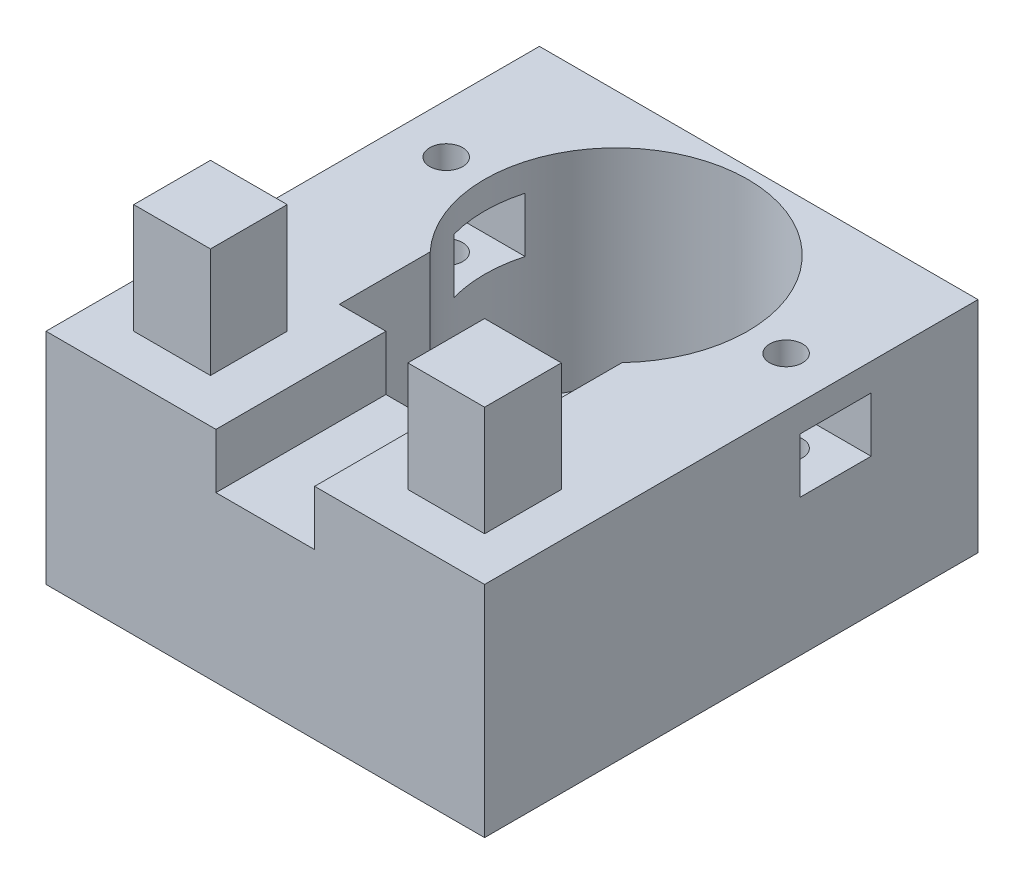
SolidWorks part; units mm, degrees
ref_plane "Plano frontal" through (0, 0, 0) normal (0, 0, 1) x (1, 0, 0)
ref_plane "Plano superior" through (0, 0, 0) normal (0, 1, 0) x (1, 0, 0)
ref_plane "Plano direito" through (0, 0, 0) normal (1, 0, 0) x (0, 0, -1)
sketch "Esboço2" plane through (0, 0, 0) normal (0, 1, 0) x (1, 0, 0)
  line L1 (0, 0) -> (40, 0)
  line L2 (0, 0) -> (0, 45)
  line L3 (0, 45) -> (40, 45)
  line L4 (40, 0) -> (40, 45)
  dimension "D1" = 40
  dimension "D2" = 45
extrude "Corpo" add sketch "Esboço2" along normal blind 20
sketch "Esboço3" plane through (0, 20, 0) normal (0, 1, 0) x (1, 0, 0)
  line L0 (20, -2.1425) -> (20, 46.202) construction
  line L1 (-2.8555, 32) -> (47.4642, 32) construction
  line L2 (40, 0) -> (40, 45) construction
  line L3 (40, 45) -> (0, 45) construction
  line L5 (11.25, 15.5) -> (28.75, 15.5)
  line L6 (11.25, 15.5) -> (11.25, 24.5)
  line L7 (11.25, 24.5) -> (28.75, 24.5)
  line L8 (28.75, 15.5) -> (28.75, 24.5)
  line L9 (11.25, 15.5) -> (28.75, 24.5) construction
  line L10 (11.25, 24.5) -> (28.75, 15.5) construction
  circle A0 centre (20, 32) radius 12
  point P10 (20, 20)
  dimension "D1" = 24
  dimension "D2" = 20
  dimension "D3" = 13
  dimension "D4" = 17.5
  dimension "D5" = 9
  dimension "D6" = 16.5
extrude "Encaixe do Motor" cut sketch "Esboço3" against normal blind 19 contours A0 L7 L6 L5 L8 | L7 A0 | L7 A0
sketch "Esboço5" plane through (0, 20, 0) normal (0, 1, 0) x (1, 0, 0)
  line L0 (41.6655, 32) -> (-3.8205, 32) construction
  line L1 (20, 57.517) -> (20, 6.483) construction
  circle A0 centre (4.5, 32) radius 1.5
  circle A1 centre (35.5, 32) radius 1.5
  point P10 (20, 32)
  dimension "D1" = 3
  dimension "D2" = 3
  dimension "D3" = 15.5
  dimension "D4" = 15.5
extrude "Corte-extrusão2" cut sketch "Esboço5" against normal through all
sketch "Esboço6" plane through (40, 0, 0) normal (1, 0, 0) x (0, 0, -1)
  line L0 (32, 21.0896) -> (32, -1.5414) construction
  line L1 (45, 20) -> (45, 0) construction
  line L2 (0, 20) -> (45, 20) construction
  line L3 (28.75, 17.5) -> (35.25, 17.5)
  line L4 (28.75, 17.5) -> (28.75, 12.5)
  line L5 (28.75, 12.5) -> (35.25, 12.5)
  line L6 (35.25, 17.5) -> (35.25, 12.5)
  line L7 (28.75, 17.5) -> (35.25, 12.5) construction
  line L8 (28.75, 12.5) -> (35.25, 17.5) construction
  point P4 (32, 15)
  dimension "D1" = 13
  dimension "D2" = 6.5
  dimension "D3" = 5
  dimension "D4" = 5
extrude "Corte-extrusão3" cut sketch "Esboço6" against normal through all
sketch "Esboço7" plane through (0, 20, 0) normal (0, 1, 0) x (1, 0, 0)
  line L0 (20, 16.9507) -> (20, -1.8604) construction
  line L1 (40, 0) -> (40, 45) construction
  line L3 (15.5, -3.2615) -> (24.5, -3.2615)
  line L4 (15.5, -3.2615) -> (15.5, 18.3519)
  line L5 (15.5, 18.3519) -> (24.5, 18.3519)
  line L6 (24.5, -3.2615) -> (24.5, 18.3519)
  line L7 (15.5, -3.2615) -> (24.5, 18.3519) construction
  line L8 (15.5, 18.3519) -> (24.5, -3.2615) construction
  point P4 (20, 7.5452)
  dimension "D1" = 20
  dimension "D2" = 9
extrude "Corte-extrusão4" cut sketch "Esboço7" against normal blind 5
sketch "Esboço8" plane through (0, 20, 0) normal (0, 1, 0) x (1, 0, 0)
  line L0 (24.5, 0) -> (40, 0) construction
  line L1 (29, 11) -> (36, 11)
  line L2 (29, 11) -> (29, 4)
  line L3 (29, 4) -> (36, 4)
  line L4 (36, 11) -> (36, 4)
  line L5 (29, 11) -> (36, 4) construction
  line L6 (29, 4) -> (36, 11) construction
  line L7 (40, 0) -> (40, 45) construction
  line L8 (0, 0) -> (15.5, 0) construction
  line L9 (4, 4) -> (11, 4)
  line L10 (4, 4) -> (4, 11)
  line L11 (4, 11) -> (11, 11)
  line L12 (11, 4) -> (11, 11)
  line L13 (4, 4) -> (11, 11) construction
  line L14 (4, 11) -> (11, 4) construction
  line L15 (0, 45) -> (0, 0) construction
  point P0 (32.5, 7.5)
  point P9 (7.5, 7.5)
  point P16 (0, 0)
  point P18 (5.8892, 5.7089)
  dimension "D1" = 7
  dimension "D2" = 7
  dimension "D3" = 7.5
  dimension "D4" = 7.5
  dimension "D5" = 7
  dimension "D6" = 7
  dimension "D7" = 7.5
  dimension "D8" = 7.5
extrude "Ressalto-extrusão2" add sketch "Esboço8" along normal blind 10
sketch "Esboço9" plane through (0, 1, 0) normal (0, 1, 0) x (1, 0, 0)
  line L0 (20, 52.9227) -> (20, 11.0773) construction
  line L1 (40, 0) -> (40, 45) construction
  line L2 (40, 45) -> (0, 45) construction
  circle A0 centre (20, 38.5) radius 3.9
  circle A1 centre (35.5, 32) radius 1.5 construction
  point P4 (20, 32)
  dimension "D2" = 7.8
  dimension "D3" = 6.5
  dimension "D4" = 20
  dimension "D5" = 6.5
  dimension "D1" = 20
